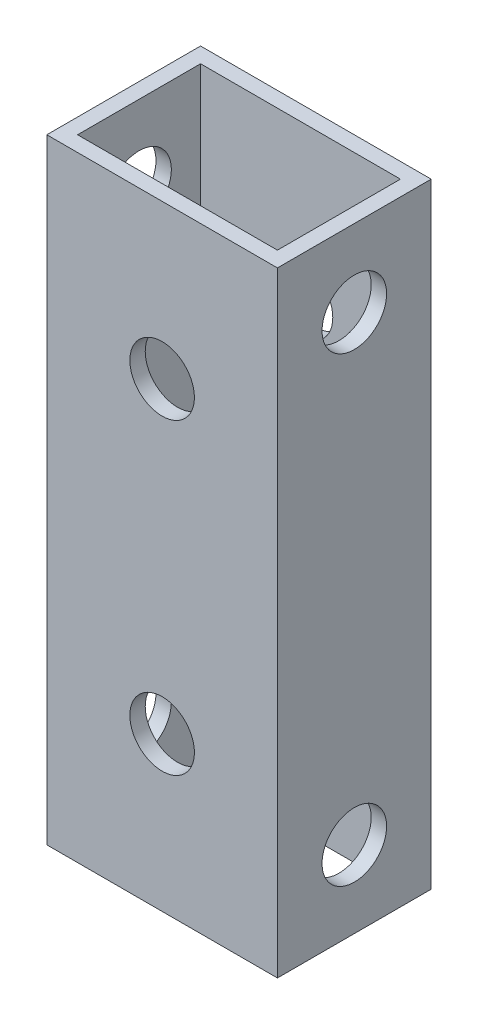
SolidWorks part; units mm, degrees
material "5052-H34"
ref_plane "正面" through (0, 0, 0) normal (0, 0, 1) x (1, 0, 0)
ref_plane "平面" through (0, 0, 0) normal (0, 1, 0) x (1, 0, 0)
ref_plane "右側面" through (0, 0, 0) normal (1, 0, 0) x (0, 0, -1)
sketch "ｽｹｯﾁ1" plane through (0, 0, 0) normal (0, 1, 0) x (1, 0, 0)
  line L1 (-7.5, 5) -> (7.5, 5)
  line L2 (-7.5, 5) -> (-7.5, -5)
  line L3 (-7.5, -5) -> (7.5, -5)
  line L4 (7.5, 5) -> (7.5, -5)
  line L5 (-7.5, 5) -> (7.5, -5) construction
  line L6 (-7.5, -5) -> (7.5, 5) construction
  point P0 (0, 0)
  dimension "D1" = 15
  dimension "D2" = 10
extrude "押し出し-薄板1" add sketch "ｽｹｯﾁ1" along normal blind 40 thin
sketch "ｽｹｯﾁ2" plane through (7.5, 0, 0) normal (1, 0, 0) x (0, 0, -1)
  line L0 (-5, 20) -> (5, 20) construction
  line L1 (-5, 40) -> (-5, 0) construction
  line L2 (5, 40) -> (5, 0) construction
  line L3 (0, 20) -> (0, 35) construction
  circle A0 centre (0, 35) radius 2.1
  circle A1 centre (0, 5) radius 2.1
  dimension "D1" = 4.2
  dimension "D2" = 30
extrude "ｶｯﾄ - 押し出し1" cut sketch "ｽｹｯﾁ2" against normal through all
sketch "ｽｹｯﾁ3" plane through (0, 0, 5) normal (0, 0, 1) x (1, 0, 0)
  line L0 (-7.5, 20) -> (7.5, 20) construction
  line L1 (-7.5, 40) -> (-7.5, 0) construction
  line L2 (7.5, 40) -> (7.5, 0) construction
  line L3 (0, 20) -> (0, 30) construction
  circle A0 centre (0, 30) radius 2.1
  circle A1 centre (0, 10) radius 2.1
  dimension "D1" = 4.2
  dimension "D2" = 20
extrude "ｶｯﾄ - 押し出し2" cut sketch "ｽｹｯﾁ3" against normal through all
